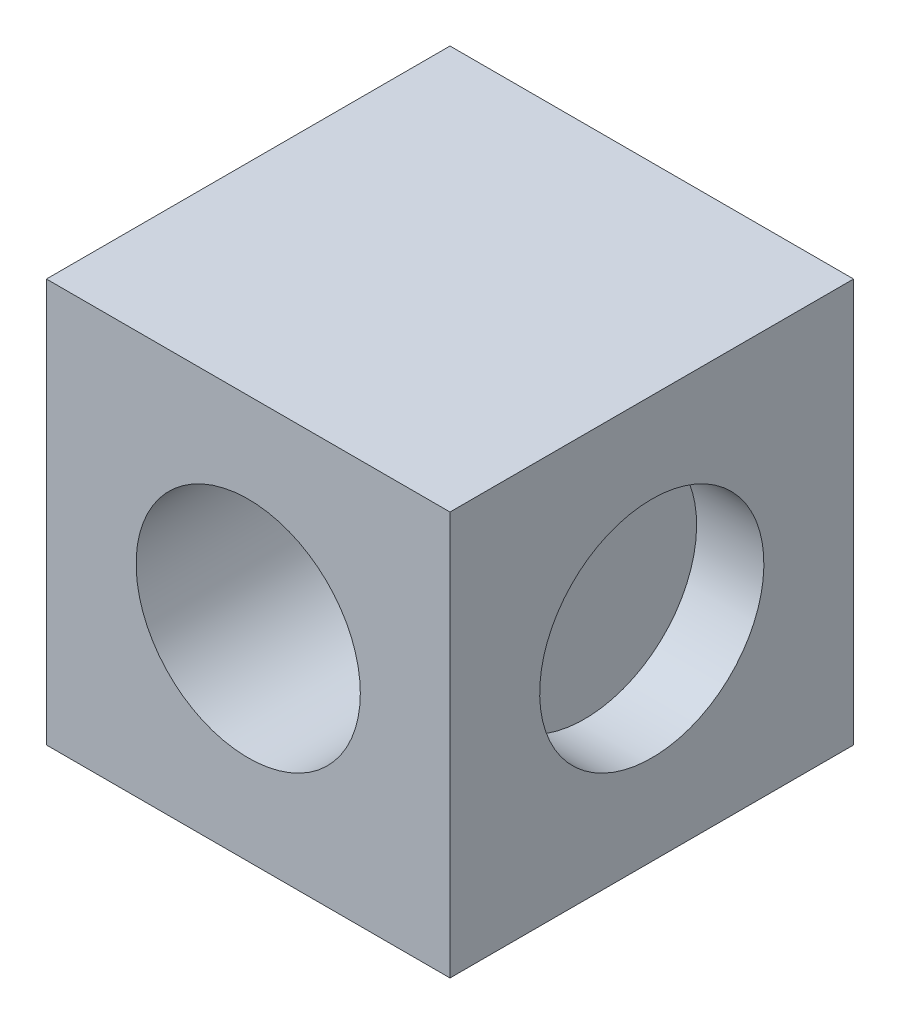
SolidWorks part; units mm, degrees
ref_plane "Front Plane" through (0, 0, 0) normal (0, 0, 1) x (1, 0, 0)
ref_plane "Top Plane" through (0, 0, 0) normal (0, 1, 0) x (1, 0, 0)
ref_plane "Right Plane" through (0, 0, 0) normal (1, 0, 0) x (0, 0, -1)
sketch "Sketch1" plane through (0, 0, 0) normal (0, 0, 1) x (1, 0, 0)
  line L1 (-9, 9) -> (9, 9)
  line L2 (-9, 9) -> (-9, -9)
  line L3 (-9, -9) -> (9, -9)
  line L4 (9, 9) -> (9, -9)
  line L5 (-9, 9) -> (9, -9) construction
  line L6 (-9, -9) -> (9, 9) construction
  circle A0 centre (0, 0) radius 5
  point P0 (0, 0)
  dimension "D3" = 10
  dimension "D1" = 18
  dimension "D2" = 18
extrude "Boss-Extrude1" add sketch "Sketch1" along normal blind 18
sketch "Sketch2" plane through (9, 0, 0) normal (1, 0, 0) x (0, 0, -1)
  line L0 (-18, -9) -> (0, -9) construction
  circle A0 centre (-9, 0) radius 5
  point P5 (-9, -9)
  dimension "D1" = 10
extrude "Cut-Extrude1" cut sketch "Sketch2" against normal blind 3
mirror "Mirror1" about plane through (0, 0, 0) normal (1, 0, 0) of "Cut-Extrude1"
